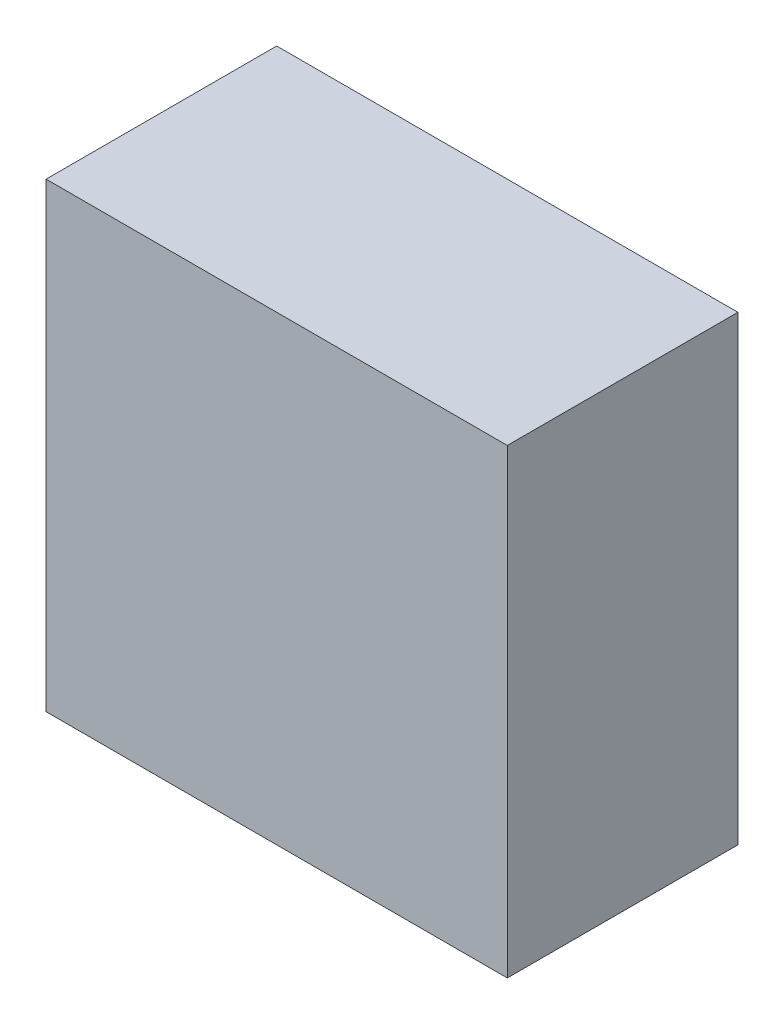
SolidWorks part; units mm, degrees
ref_plane "Front Plane" through (0, 0, 0) normal (0, 0, 1) x (1, 0, 0)
ref_plane "Top Plane" through (0, 0, 0) normal (0, 1, 0) x (1, 0, 0)
ref_plane "Right Plane" through (0, 0, 0) normal (1, 0, 0) x (0, 0, -1)
sketch "Sketch1" plane through (0, 0, 0) normal (0, 0, 1) x (1, 0, 0)
  line L1 (0, 0) -> (3048, 0)
  line L2 (0, 0) -> (0, 3048)
  line L3 (0, 3048) -> (3048, 3048)
  line L4 (3048, 0) -> (3048, 3048)
extrude "Boss-Extrude1" add sketch "Sketch1" along normal blind 1524
